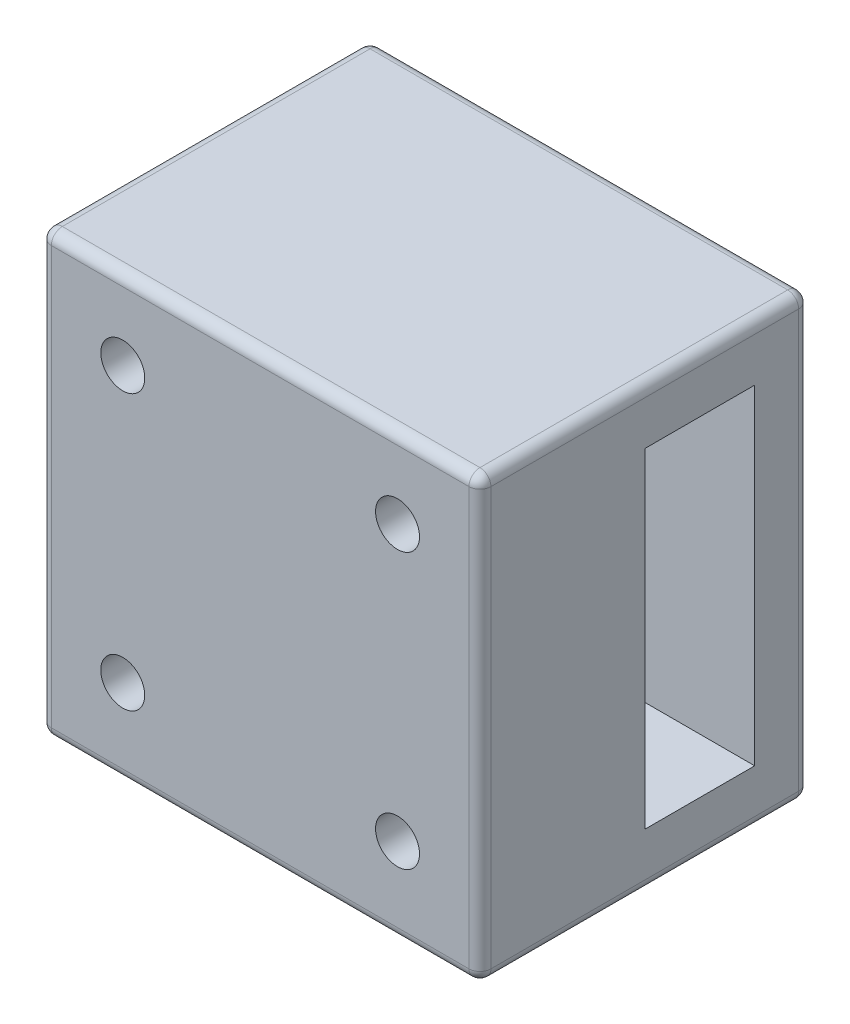
SolidWorks part; units mm, degrees
ref_plane "Front Plane" through (0, 0, 0) normal (0, 0, 1) x (1, 0, 0)
ref_plane "Top Plane" through (0, 0, 0) normal (0, 1, 0) x (1, 0, 0)
ref_plane "Right Plane" through (0, 0, 0) normal (1, 0, 0) x (0, 0, -1)
sketch "Sketch2" plane through (0, 0, 0) normal (0, 1, 0) x (1, 0, 0)
  line L1 (20, 15) -> (-20, 15)
  line L2 (20, 15) -> (20, -15)
  line L3 (20, -15) -> (-20, -15)
  line L4 (-20, 15) -> (-20, -15)
  line L5 (20, 15) -> (-20, -15) construction
  line L6 (20, -15) -> (-20, 15) construction
  point P0 (0, 0)
  dimension "D1" = 40
  dimension "30" = 30
extrude "Boss-Extrude1" add sketch "Sketch2" along normal blind 40
sketch "Sketch3" plane through (20, 0, 0) normal (1, 0, 0) x (0, 0, -1)
  line L0 (15, 40) -> (15, 0) construction
  line L1 (0, 35) -> (10, 35)
  line L2 (0, 35) -> (0, 5)
  line L3 (0, 5) -> (10, 5)
  line L4 (10, 35) -> (10, 5)
  line L5 (-15, 0) -> (15, 0) construction
  dimension "D1" = 5
  dimension "D2" = 30
  dimension "D3" = 5
  dimension "D4" = 10
extrude "Cut-Extrude1" cut sketch "Sketch3" against normal blind 40
sketch "Sketch5" plane through (0, 0, 15) normal (0, 0, 1) x (1, 0, 0)
  line L0 (20, 40) -> (20, 0) construction
  line L1 (-20, 40) -> (20, 40) construction
  circle A0 centre (12.5, 7.8) radius 2
  circle A1 centre (12.5, 32.8) radius 2
  circle A2 centre (-12.5, 32.8) radius 2
  circle A3 centre (-12.5, 7.8) radius 2
  point P12 (0, 0)
  point P13 (-12.5, 32.8)
  point P14 (0, 0)
  dimension "D1" = 4
  dimension "D2" = 4
  dimension "D7" = 4
  dimension "D8" = 4
  dimension "D3" = 25
  dimension "D4" = 7.5
  dimension "D5" = 25
  dimension "D6" = 7.2
extrude "Cut-Extrude2" cut sketch "Sketch5" against normal up to next
fillet "Fillet2" radius 1 12 edges at (-20, 0, 0) (0, 0, 15) (20, 0, 0) (0, 0, -15) (-20, 40, 0) (0, 40, 15) (0, 40, -15) (-20, 20, -15) (20, 20, -15) (20, 20, 15) (-20, 20, 15) (20, 40, 0)
